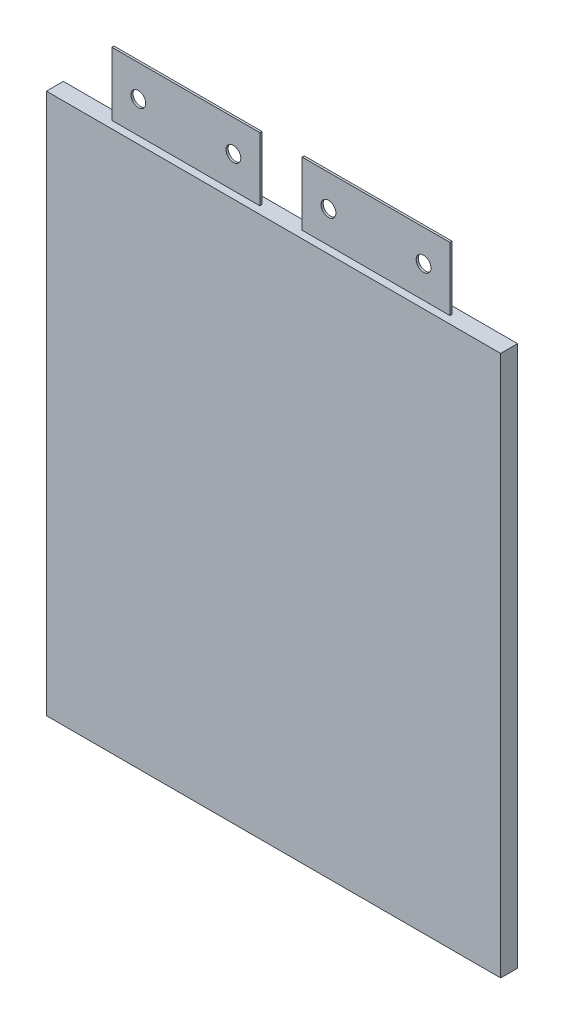
SolidWorks part; units mm, degrees
ref_plane "Front Plane" through (0, 0, 0) normal (0, 0, 1) x (1, 0, 0)
ref_plane "Top Plane" through (0, 0, 0) normal (0, 1, 0) x (1, 0, 0)
ref_plane "Right Plane" through (0, 0, 0) normal (1, 0, 0) x (0, 0, -1)
sketch "Sketch2" plane through (0, 0, 0) normal (0, 0, 1) x (1, 0, 0)
  line L1 (0, 0) -> (215, 0)
  line L2 (0, 0) -> (0, 256)
  line L3 (0, 256) -> (215, 256)
  line L4 (215, 0) -> (215, 256)
  dimension "D1" = 256
  dimension "D2" = 215
extrude "Boss-Extrude1" add sketch "Sketch2" along normal blind 8
sketch "Sketch3" plane through (0, 256, 0) normal (0, 1, 0) x (1, 0, 0)
  line L0 (0, -4) -> (215, -4) construction
  line L1 (0, -8) -> (0, 0) construction
  line L2 (215, -8) -> (215, 0) construction
  line L3 (107.5, 0) -> (107.5, -8) construction
  line L4 (27.5, -3.5) -> (97.5, -3.5)
  line L5 (27.5, -3.5) -> (27.5, -4.5)
  line L6 (27.5, -4.5) -> (97.5, -4.5)
  line L7 (97.5, -3.5) -> (97.5, -4.5)
  line L8 (215, 0) -> (0, 0) construction
  line L9 (215, -8) -> (0, -8) construction
  line L10 (117.5, -3.5) -> (117.5, -4.5)
  line L11 (187.5, -4.5) -> (117.5, -4.5)
  line L12 (187.5, -3.5) -> (117.5, -3.5)
  line L13 (187.5, -3.5) -> (187.5, -4.5)
  point P10 (7.9933, -4)
  point P11 (27.5, -4)
  dimension "D1" = 1
  dimension "D2" = 70
  dimension "D3" = 10
extrude "Boss-Extrude3" add sketch "Sketch3" along normal blind 30 contours L6 L7 L4 L5 | L12 L10 L11 L13
sketch "Sketch5" plane through (0, 0, 4.5) normal (0, 0, 1) x (1, 0, 0)
  line L0 (27.5, 271) -> (97.5, 271) construction
  line L1 (27.5, 286) -> (27.5, 256) construction
  line L2 (97.5, 286) -> (97.5, 256) construction
  line L3 (62.5, 286) -> (62.5, 256) construction
  line L4 (27.5, 286) -> (97.5, 286) construction
  line L5 (27.5, 256) -> (97.5, 256) construction
  circle A0 centre (40, 271) radius 3.5
  circle A1 centre (85, 271) radius 3.5
  dimension "D1" = 7
  dimension "D2" = 7
  dimension "D3" = 45
  dimension "D4" = 22.5
ref_plane "Plane1" through (107.5, 0, 0) normal (1, 0, 0) x (0, 0, -1)
extrude "Cut-Extrude1" cut sketch "Sketch5" against normal up to next contours A0 | A1
mirror "Mirror1" about plane through (107.5, 0, 0) normal (1, 0, 0) of "Cut-Extrude1"
